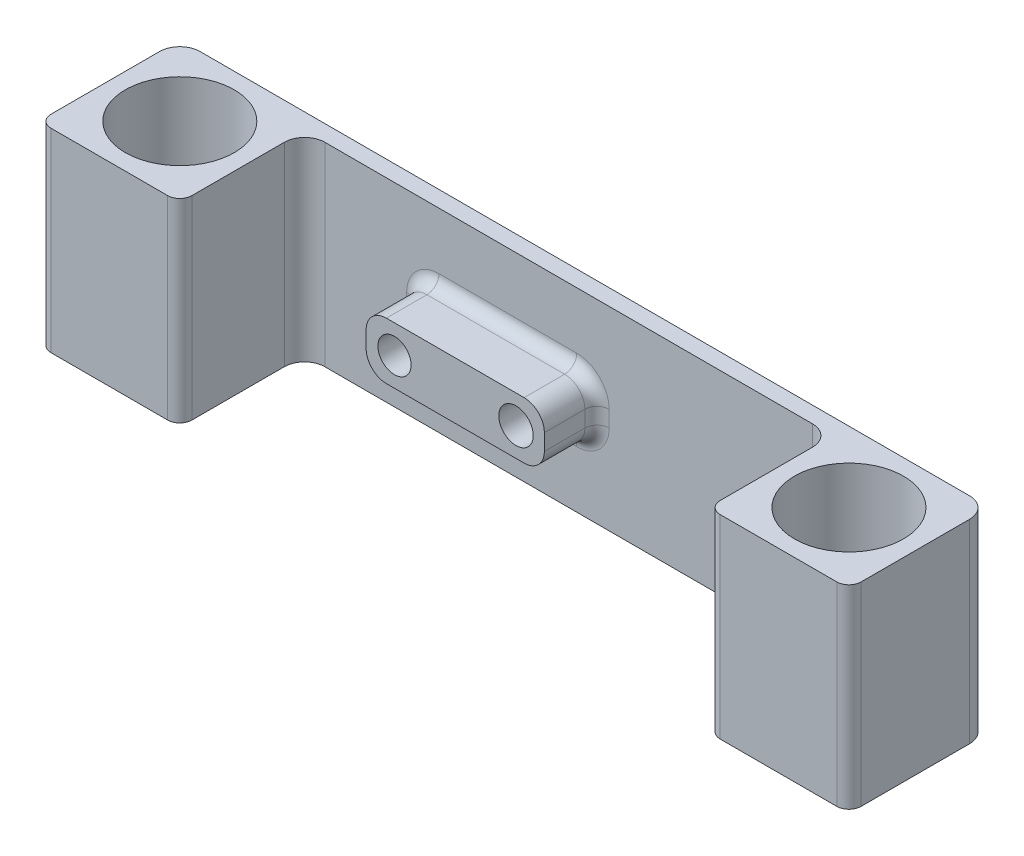
SolidWorks part; units mm, degrees
ref_plane "Front Plane" through (0, 0, 0) normal (0, 0, 1) x (1, 0, 0)
ref_plane "Top Plane" through (0, 0, 0) normal (0, 1, 0) x (1, 0, 0)
ref_plane "Right Plane" through (0, 0, 0) normal (1, 0, 0) x (0, 0, -1)
sketch "Sketch1" plane through (0, 0, 0) normal (0, 1, 0) x (1, 0, 0)
  line L1 (-17.4, 17.4) -> (17.4, 17.4)
  line L2 (-17.4, 13.4) -> (-17.4, -17.4)
  line L3 (-17.4, -17.4) -> (17.4, -17.4)
  line L4 (17.4, 17.4) -> (17.4, -17.4)
  line L5 (0, -17.4) -> (0, 17.4) construction
  line L6 (-17.4, 0) -> (17.4, 0) construction
  line L7 (-17.4, 17.4) -> (-82.6, 17.4)
  line L9 (-17.4, 13.4) -> (-82.6, 13.4)
  line L10 (-82.6, 17.4) -> (-82.6, 13.4)
  circle A0 centre (0, 0) radius 13.45
  dimension "D1" = 26.9
  dimension "D2" = 34.8
  dimension "D3" = 34.8
  dimension "D4" = 65.2
  dimension "D5" = 4
extrude "Boss-Extrude2" add sketch "Sketch1" along normal blind 48
mirror "Mirror2" about plane through (-82.6, 48, -17.4) normal (1, 0, 0) of "Boss-Extrude2"
sketch "Sketch7" plane through (0, 0, -13.4) normal (0, 0, 1) x (1, 0, 0)
  line L0 (-147.8, 24) -> (-17.4, 24) construction
  line L1 (-147.8, 48) -> (-147.8, 0) construction
  line L2 (-17.4, 48) -> (-17.4, 0) construction
  line L3 (-82.6, 48) -> (-82.6, 0) construction
  line L4 (-147.8, 48) -> (-17.4, 48) construction
  line L5 (-147.8, 0) -> (-17.4, 0) construction
  line L6 (-112.6, 24) -> (-82.6, 24) construction
  line L8 (-119.6, 17) -> (-75.6, 17)
  line L9 (-119.6, 17) -> (-119.6, 31)
  line L10 (-119.6, 31) -> (-75.6, 31)
  line L11 (-75.6, 17) -> (-75.6, 31)
  line L12 (-97.6, 31) -> (-97.6, 17) construction
  line L13 (-119.6, 24) -> (-75.6, 24) construction
  circle A0 centre (-82.6, 24) radius 4.25
  circle A2 centre (-112.6, 24) radius 4.1
  point P15 (-97.6, 24)
  dimension "D1" = 8.5
  dimension "D3" = 8.2
  dimension "D5" = 30
  dimension "D2" = 14
  dimension "D4" = 44
extrude "Boss-Extrude3" add sketch "Sketch7" along normal blind 13
fillet "Fillet1" radius 3 4 edges at (17.4, 24, 17.4) (-17.4, 24, 17.4) (-182.6, 24, 17.4) (-147.8, 24, 17.4)
fillet "Fillet2" radius 5 4 edges at (-17.4, 24, -13.4) (17.4, 24, -17.4) (-182.6, 24, -17.4) (-147.8, 24, -13.4)
fillet "Fillet3" radius 5 4 edges at (-75.6, 31, -6.9) (-75.6, 17, -6.9) (-119.6, 31, -6.9) (-119.6, 17, -6.9)
fillet "Fillet4" radius 3 8 edges at (-118.1355, 18.4645, -13.4) (-119.6, 24, -13.4) (-118.1355, 29.5355, -13.4) (-97.6, 31, -13.4) (-77.0645, 29.5355, -13.4) (-75.6, 24, -13.4) (-77.0645, 18.4645, -13.4) (-97.6, 17, -13.4)
